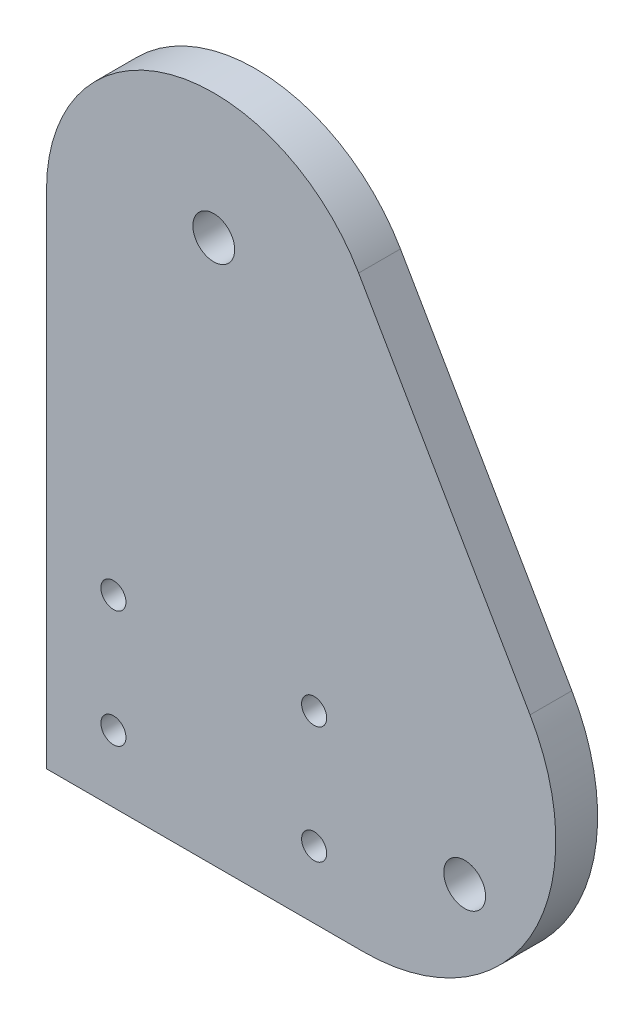
SolidWorks part; units mm, degrees
ref_plane "前基準面" through (0, 0, 0) normal (0, 0, 1) x (1, 0, 0)
ref_plane "上基準面" through (0, 0, 0) normal (0, 1, 0) x (1, 0, 0)
ref_plane "右基準面" through (0, 0, 0) normal (1, 0, 0) x (0, 0, -1)
sketch "草圖1" plane through (0, 0, 0) normal (0, 0, 1) x (1, 0, 0)
  line L0 (-20, 0) -> (20, 0) construction
  line L2 (-20, 30) -> (-20, -30)
  line L4 (20, 0.359) -> (20, 0)
  line L5 (-20, 30) -> (20, -30) construction
  line L6 (-20, -30) -> (20, 30) construction
  line L7 (0, 25) -> (0, 50025) construction
  line L8 (0, 35) -> (30, -16.9615) construction
  line L9 (-20, -30) -> (17.8979, -30)
  line L10 (37.8164, 4.5) -> (17.3205, 40)
  arc A1 (17.3205, 40) -> (-20, 30) centre (0, 30) ccw
  circle A2 centre (-12, -8) radius 1.5
  circle A3 centre (-12, -22) radius 1.5
  circle A4 centre (12, -22) radius 1.5
  circle A5 centre (12, -8) radius 1.5
  circle A7 centre (0, 35) radius 2.5
  circle A8 centre (30, -16.9615) radius 2.5
  arc A9 (17.8979, -30) -> (37.8164, 4.5) centre (17.8979, -7) ccw
  point P0 (0, 0)
  dimension "D2" = 20
  dimension "D4" = 3
  dimension "D8" = 5
  dimension "D9" = 5
  dimension "D12" = 5
  dimension "D3" = 23
  dimension "D5" = 8
  dimension "D6" = 8
  dimension "D7" = 60
  dimension "D10" = 60
  dimension "D11" = 30
  dimension "D13" = 40
  dimension "D14" = 30
  dimension "D15" = 8
extrude "填料-伸長2" add sketch "草圖1" along normal blind 5
